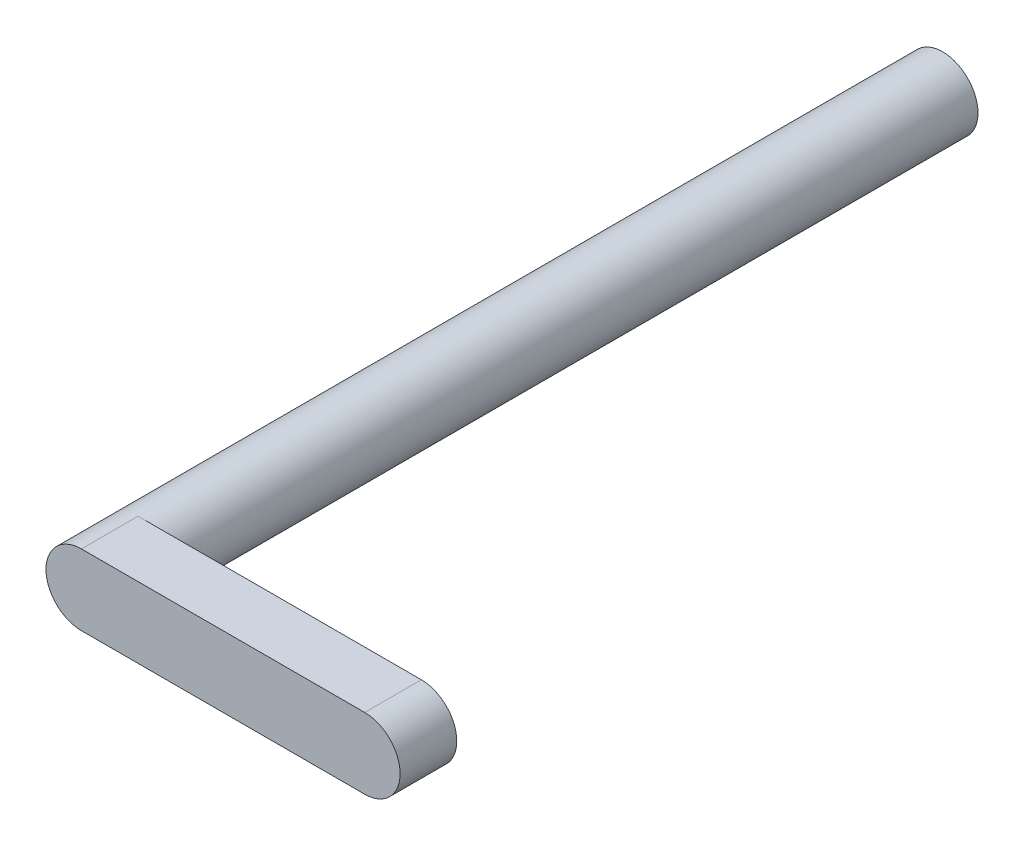
SolidWorks part; units mm, degrees
ref_plane "Front Plane" through (0, 0, 0) normal (0, 0, 1) x (1, 0, 0)
ref_plane "Top Plane" through (0, 0, 0) normal (0, 1, 0) x (1, 0, 0)
ref_plane "Right Plane" through (0, 0, 0) normal (1, 0, 0) x (0, 0, -1)
sketch "Sketch1" plane through (0, 0, 0) normal (0, 0, 1) x (1, 0, 0)
  circle A0 centre (0, 0) radius 0.7937
  dimension "D1" = 1.5875
extrude "Boss-Extrude1" add sketch "Sketch1" along normal blind 19.304
sketch "Sketch3" plane through (0, 0, 19.304) normal (0, 0, 1) x (1, 0, 0)
  line L0 (0, 0.7937) -> (6.35, 0.7938)
  line L1 (0, -0.7937) -> (6.35, -0.7938)
  arc A0 (0, 0.7937) -> (0, -0.7937) centre (0, 0) ccw
  arc A1 (6.35, -0.7938) -> (6.35, 0.7938) centre (6.35, 0) ccw
  dimension "D1" = 1.5875
  dimension "D2" = 1.5875
  dimension "D3" = 6.35
extrude "Boss-Extrude5" add sketch "Sketch3" against normal blind 1.27 contours L0 A1 L1 A0
